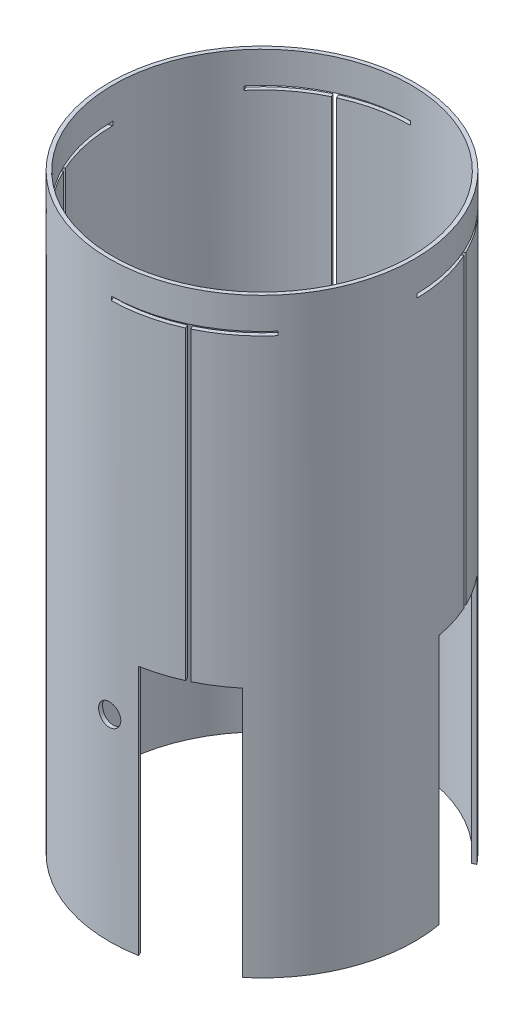
SolidWorks part; units mm, degrees
material "Corrugated Paper"
ref_plane "Front Plane" through (0, 0, 0) normal (0, 0, 1) x (1, 0, 0)
ref_plane "Top Plane" through (0, 0, 0) normal (0, 1, 0) x (1, 0, 0)
ref_plane "Right Plane" through (0, 0, 0) normal (1, 0, 0) x (0, 0, -1)
sketch "Sketch1" plane through (0, 0, 0) normal (0, 0, 1) x (1, 0, 0)
  line L0 (0, 0) -> (0, 156.4586) construction
  line L1 (0, 239.72) -> (-60.325, 239.72) construction
  line L2 (-60.325, 239.72) -> (-60.325, 238.1325)
  line L3 (-60.325, 239.72) -> (-61.9125, 239.72)
  line L4 (-61.9125, 239.72) -> (-61.9125, 0)
  line L5 (-61.9125, 0) -> (-60.325, 0)
  line L6 (-60.325, 0) -> (-60.325, 238.1325)
  line L7 (-60.325, 238.1325) -> (0, 238.1325) construction
  line L8 (0, 238.1325) -> (0, 239.72) construction
  line L9 (0, 0) -> (-60.325, 0) construction
  line L10 (-60.325, 0) -> (-60.325, 76.2) construction
  line L11 (-60.325, 76.2) -> (-62.1538, 76.2) construction
  line L12 (-62.1538, 76.2) -> (-62.1538, 83.2) construction
  line L13 (-62.1538, 83.2) -> (-60.325, 83.2) construction
  line L14 (-60.325, 83.2) -> (-60.325, 93.67) construction
  line L15 (-60.325, 93.67) -> (0, 93.67) construction
  point P18 (-62.1538, 79.7)
  dimension "D1" = 120.65
  dimension "D2" = 123.825
  dimension "D3" = 7
  dimension "D4" = 13.97
  dimension "D5" = 1.8288
  dimension "D6" = 76.2
  dimension "D7" = 144.4625
revolve "Revolve1" add sketch "Sketch1" angle 360 about L0
ref_plane "Plane1" through (0, 0, 0) normal (0.4226, 0, 0.9063) x (0, -1, 0)
sketch "Sketch2" plane through (0, 0, 0) normal (0, 0, 1) x (1, 0, 0)
  line L0 (0, 0) -> (0, 156.4586) construction
  circle A0 centre (0, 79.7) radius 4.5
  dimension "D1" = 9
extrude "Cut-Extrude1" cut sketch "Sketch2" against normal through all and the other way through all
sketch "Sketch3" plane through (0, 0, 0) normal (0.4226, 0, 0.9063) x (0.9063, 0, -0.4226)
  line L0 (-15.875, 0) -> (-15.875, 101.6)
  line L1 (-15.875, 0) -> (15.875, 0)
  line L2 (-0.7937, 225.4325) -> (0.7937, 225.4325) construction
  line L3 (-15.875, 101.6) -> (-0.7937, 101.6)
  line L4 (-61.9125, 0) -> (61.9125, 0) construction
  line L5 (0.7937, 225.4325) -> (25.4, 225.4325)
  line L6 (25.4, 225.4325) -> (25.4, 227.02)
  line L7 (25.4, 227.02) -> (-25.4, 227.02)
  line L8 (-25.4, 227.02) -> (-25.4, 225.4325)
  line L9 (-25.4, 225.4325) -> (-0.7937, 225.4325)
  line L11 (-0.7937, 101.6) -> (-0.7937, 225.4325)
  line L12 (15.875, 0) -> (15.875, 101.6)
  line L13 (15.875, 101.6) -> (0.7937, 101.6)
  line L14 (0.7937, 101.6) -> (0.7937, 225.4325)
  line L15 (-0.7937, 101.6) -> (0.7937, 101.6) construction
  line L16 (61.9125, 239.72) -> (-61.9125, 239.72) construction
  dimension "D1" = 31.75
  dimension "D2" = 50.8
  dimension "D3" = 12.7
  dimension "D4" = 1.5875
  dimension "D5" = 101.6
extrude "Cut-Extrude2" cut sketch "Sketch3" against normal through all
pattern_circular "CirPattern1" count 4 over 360 about axis through (0, 0, 0) along (0, 1, 0) of "Cut-Extrude2"
